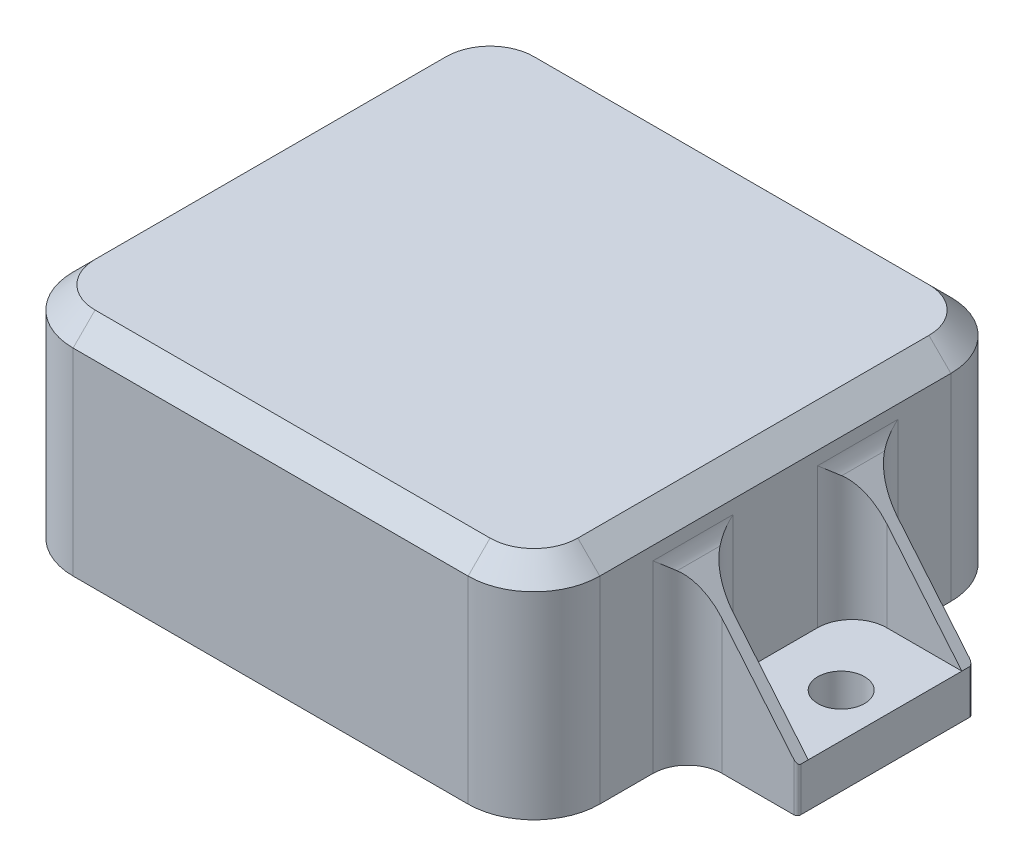
SolidWorks part; units mm, degrees
ref_plane "Front Plane" through (0, 0, 0) normal (0, 0, 1) x (1, 0, 0)
ref_plane "Top Plane" through (0, 0, 0) normal (0, 1, 0) x (1, 0, 0)
ref_plane "Right Plane" through (0, 0, 0) normal (1, 0, 0) x (0, 0, -1)
sketch "Sketch1" plane through (0, 0, 0) normal (0, 1, 0) x (1, 0, 0)
  line L1 (-38.1, 34.925) -> (38.1, 34.925)
  line L2 (-38.1, 34.925) -> (-38.1, -34.925)
  line L3 (-38.1, -34.925) -> (38.1, -34.925)
  line L4 (38.1, 34.925) -> (38.1, -34.925)
  line L5 (-38.1, 34.925) -> (38.1, -34.925) construction
  line L6 (-38.1, -34.925) -> (38.1, 34.925) construction
  point P0 (0, 0)
  dimension "D1" = 69.85
  dimension "D2" = 76.2
extrude "Boss-Extrude1" add sketch "Sketch1" along normal blind 31.75
fillet "Fillet1" radius 9.525 4 edges at (-38.1, 15.875, -34.925) (38.1, 15.875, -34.925) (38.1, 15.875, 34.925) (-38.1, 15.875, 34.925)
sketch "Sketch2" plane through (0, 0, 0) normal (0, -1, 0) x (1, 0, 0)
  line L8 (31.75, -25.4) -> (31.75, 25.4)
  line L9 (-28.575, -28.575) -> (28.575, -28.575)
  line L10 (-31.75, 25.4) -> (-31.75, -25.4)
  line L11 (28.575, 28.575) -> (-28.575, 28.575)
  line L12 (31.75, -25.4) -> (31.75, 25.4)
  line L13 (-28.575, -28.575) -> (28.575, -28.575)
  line L14 (-31.75, 25.4) -> (-31.75, -25.4)
  line L15 (28.575, 28.575) -> (-28.575, 28.575)
  arc A8 (31.75, 25.4) -> (28.575, 28.575) centre (28.575, 25.4) ccw
  arc A9 (28.575, -28.575) -> (31.75, -25.4) centre (28.575, -25.4) ccw
  arc A10 (-31.75, -25.4) -> (-28.575, -28.575) centre (-28.575, -25.4) ccw
  arc A11 (-28.575, 28.575) -> (-31.75, 25.4) centre (-28.575, 25.4) ccw
  arc A12 (31.75, 25.4) -> (28.575, 28.575) centre (28.575, 25.4) ccw
  arc A13 (28.575, -28.575) -> (31.75, -25.4) centre (28.575, -25.4) ccw
  arc A14 (-31.75, -25.4) -> (-28.575, -28.575) centre (-28.575, -25.4) ccw
  arc A15 (-28.575, 28.575) -> (-31.75, 25.4) centre (-28.575, 25.4) ccw
  dimension "D2" = 3.175
  dimension "D1" = 6.35
extrude "Cut-Extrude1" cut sketch "Sketch2" against normal offset from surface (28.575 mm away) 3.175 up to face at (0, 31.75, 0)
sketch "Sketch11" plane through (0, 0, 0) normal (0, -1, 0) x (1, 0, 0)
  line L8 (36.5125, -25.4) -> (36.5125, 25.4)
  line L9 (-28.575, -33.3375) -> (28.575, -33.3375)
  line L10 (-36.5125, 25.4) -> (-36.5125, -25.4)
  line L11 (28.575, 33.3375) -> (-28.575, 33.3375)
  line L12 (36.5125, -25.4) -> (36.5125, 25.4)
  line L13 (-28.575, -33.3375) -> (28.575, -33.3375)
  line L14 (-36.5125, 25.4) -> (-36.5125, -25.4)
  line L15 (28.575, 33.3375) -> (-28.575, 33.3375)
  arc A8 (36.5125, 25.4) -> (28.575, 33.3375) centre (28.575, 25.4) ccw
  arc A9 (28.575, -33.3375) -> (36.5125, -25.4) centre (28.575, -25.4) ccw
  arc A10 (-36.5125, -25.4) -> (-28.575, -33.3375) centre (-28.575, -25.4) ccw
  arc A11 (-28.575, 33.3375) -> (-36.5125, 25.4) centre (-28.575, 25.4) ccw
  arc A12 (36.5125, 25.4) -> (28.575, 33.3375) centre (28.575, 25.4) ccw
  arc A13 (28.575, -33.3375) -> (36.5125, -25.4) centre (28.575, -25.4) ccw
  arc A14 (-36.5125, -25.4) -> (-28.575, -33.3375) centre (-28.575, -25.4) ccw
  arc A15 (-28.575, 33.3375) -> (-36.5125, 25.4) centre (-28.575, 25.4) ccw
  dimension "D1" = 1.5875
extrude "Cut-Extrude3" cut sketch "Sketch11" against normal blind 4.7625
ref_plane "Plane1" through (0, 0, 0) normal (0, 0, 1) x (1, 0, 0)
sketch "Sketch4" plane through (0, 0, 0) normal (0, 0, 1) x (1, 0, 0)
  line L0 (-38.1, 0) -> (-53.975, 0)
  line L1 (-53.975, 0) -> (-53.975, 6.35)
  line L2 (-53.975, 6.35) -> (-38.1, 25.4)
  line L3 (-38.1, 0) -> (-38.1, 31.75) construction
  line L4 (-38.1, 25.4) -> (-38.1, 0)
  line L5 (-47.625, -1007.4222) -> (-47.625, 48992.5778) construction
  dimension "D1" = 6.35
  dimension "D2" = 47.625
  dimension "D3" = 25.4
  dimension "D4" = 6.35
extrude "Boss-Extrude3" add sketch "Sketch4" along normal mid plane 25.4
hole_wizard "1/4 Clearance Hole2" positions "Sketch8" profile "Sketch9" hole size "1/4" standard "ANSI Inch" end condition through all
sketch "Sketch8" plane through (-13.567, 0, 0) normal (0, 1, 0) x (1, 0, 0)
  line L0 (-3.8955, 0) -> (31.0295, 0) construction
  point P0 (-34.058, 0)
  dimension "D1" = 47.625
sketch "Sketch9" plane through (-47.625, 0, 0) normal (1, 0, 0) x (0, 0, -1)
  line L0 (0, 0) -> (0, 31.75)
  line L1 (0, 31.75) -> (3.3782, 31.75)
  line L2 (3.3782, 31.75) -> (3.3782, 0)
  line L5 (3.3782, 0) -> (0, 0)
  line L11 (0, -6.35) -> (0, 107.95) construction
  dimension "Thru Hole Dia." = 6.7564
  dimension "Thru Hole Depth" = 31.75
sketch "Sketch15" plane through (-38.1, 0, 0) normal (-1, 0, 0) x (0, 0, 1)
  line L0 (12.7, 6.35) -> (-12.7, 6.35) construction
  line L1 (-11.1125, 25.4) -> (11.1125, 25.4)
  line L2 (-11.1125, 25.4) -> (-11.1125, 6.35)
  line L3 (-11.1125, 6.35) -> (11.1125, 6.35)
  line L4 (11.1125, 25.4) -> (11.1125, 6.35)
  line L5 (-11.1125, 25.4) -> (11.1125, 6.35) construction
  line L6 (-11.1125, 6.35) -> (11.1125, 25.4) construction
  line L7 (12.7, 25.4) -> (-12.7, 25.4) construction
  line L8 (12.7, 25.4) -> (12.7, 6.35) construction
  point P0 (0, 15.875)
  point P5 (0, 0)
  dimension "D1" = 1.5875
extrude "Cut-Extrude5" cut sketch "Sketch15" along normal through all
mirror "Mirror4" about plane through (0, 0, 0) normal (1, 0, 0) of "Cut-Extrude5", "Boss-Extrude3", "1/4 Clearance Hole2"
fillet "Fillet2" radius 5.0165 8 edges at (-38.1, 15.875, -11.1125) (-38.1, 15.875, 11.1125) (-38.1, 12.7, 12.7) (-38.1, 12.7, -12.7) (38.1, 12.7, 12.7) (38.1, 15.875, -11.1125) (38.1, 12.7, -12.7) (38.1, 15.875, 11.1125)
fillet "Fillet3" radius 3.429 4 edges at (-38.1, 25.4, 11.9062) (-38.1, 25.4, -11.9062) (38.1, 25.4, -11.9062) (38.1, 25.4, 11.9062)
fillet "Fillet4" radius 0.508 4 edges at (53.975, 3.175, 12.7) (53.975, 3.175, -12.7) (-53.975, 3.175, 12.7) (-53.975, 3.175, -12.7)
chamfer "Chamfer1" distance 3.175 angle 45 8 edges at (0, 31.75, -34.925) (-35.3102, 31.75, -32.1352) (35.3102, 31.75, -32.1352) (-38.1, 31.75, 0) (38.1, 31.75, 0) (-35.3102, 31.75, 32.1352) (35.3102, 31.75, 32.1352) (0, 31.75, 34.925)
hole_wizard "#2-56 Tapped Hole1" positions "Sketch12" profile "Sketch13" tap size "#2-56" standard "ANSI Inch"
sketch "Sketch12" plane through (0, 4.7625, 0) normal (0, -1, 0) x (-1, 0, 0)
  line L0 (31.75, 25.4) -> (31.75, -25.4) construction
  line L1 (-28.575, -28.575) -> (28.575, -28.575) construction
  point P0 (15.875, -30.607)
  point P2 (33.782, -15.875)
  dimension "D1" = 2.032
  dimension "D2" = 2.032
  dimension "D3" = 15.875
  dimension "D4" = 15.875
sketch "Sketch13" plane through (-15.875, 4.7625, 30.607) normal (1, 0, 0) x (0, 0, -1)
  line L0 (0, 0) -> (0, 6.1222)
  line L1 (0, 6.1222) -> (0.889, 5.588)
  line L2 (0.889, 5.588) -> (0.889, 0)
  line L5 (0.889, 0) -> (0, 0)
  line L10 (0, 6.1222) -> (-0.889, 5.588) construction
  line L11 (0, -6.35) -> (0, 107.95) construction
  dimension "Tap Drill Dia." = 1.778
  dimension "Tap Drill Depth" = 5.588
  dimension "Drill Angle" = 118
cosmetic thread "Hole Thread1" parameters "D1"=4.318, "D2"=2.1844
cosmetic thread "Hole Thread2" parameters "D1"=4.318, "D2"=2.1844
mirror "Mirror2" about plane through (0, 0, 0) normal (0, 0, 1) of "#2-56 Tapped Hole1"
mirror "Mirror3" about plane through (0, 0, 0) normal (1, 0, 0) of "Mirror2", "#2-56 Tapped Hole1"
sketch "Sketch14" plane through (0, 0, -34.925) normal (0, 0, -1) x (-1, 0, 0)
  line L0 (-28.575, 0) -> (28.575, 0) construction
  line L1 (-15.875, 15.875) -> (0, 0) construction
  line L2 (0, 0) -> (15.875, 15.875) construction
  circle A0 centre (-15.875, 15.875) radius 6.35
  circle A1 centre (15.875, 15.875) radius 6.35
  dimension "D1" = 12.7
  dimension "D2" = 15.875
  dimension "D3" = 15.875
extrude "Cut-Extrude4" cut sketch "Sketch14" against normal up to next
hole_wizard "#4-40 Tapped Hole1" positions "Sketch16" profile "Sketch17" tap size "#4-40" standard "ANSI Inch"
sketch "Sketch16" plane through (-13.4356, -50.4496, -34.925) normal (0, 0, -1) x (-1, 0, 0)
  point P0 (-5.1044, 73.8684)
  point P2 (9.9832, 73.8684)
  point P4 (9.9832, 58.7808)
  point P6 (-5.1044, 58.7808)
  point P8 (-21.7668, 58.7808)
  point P10 (-21.7668, 73.8684)
  point P12 (-36.8544, 73.8684)
  point P14 (-36.8544, 58.7808)
  point P19 (0, 0)
  point P22 (0, 0)
  point P25 (0, 0)
  point P28 (0, 0)
  point P31 (0, 0)
  point P34 (0, 0)
  point P37 (0, 0)
sketch "Sketch17" plane through (-8.3312, 23.4188, -34.925) normal (1, 0, 0) x (0, 1, 0)
  line L0 (0, 0) -> (0, 7.0282)
  line L1 (0, 7.0282) -> (1.1303, 6.349)
  line L2 (1.1303, 6.349) -> (1.1303, 0)
  line L3 (1.1303, 0) -> (0, 0)
  line L4 (0, 7.0282) -> (-1.1303, 6.349) construction
  line L5 (0, -6.35) -> (0, 107.95) construction
  dimension "Tap Drill Dia." = 2.2606
  dimension "Tap Drill Depth" = 6.349
  dimension "Drill Angle" = 118
cosmetic thread "Hole Thread3" parameters "D1"=5.588, "D2"=2.8448
cosmetic thread "Hole Thread4" parameters "D1"=5.588, "D2"=2.8448
cosmetic thread "Hole Thread5" parameters "D1"=5.588, "D2"=2.8448
cosmetic thread "Hole Thread6" parameters "D1"=5.588, "D2"=2.8448
cosmetic thread "Hole Thread7" parameters "D1"=5.588, "D2"=2.8448
cosmetic thread "Hole Thread8" parameters "D1"=5.588, "D2"=2.8448
cosmetic thread "Hole Thread9" parameters "D1"=5.588, "D2"=2.8448
cosmetic thread "Hole Thread10" parameters "D1"=5.588, "D2"=2.8448
